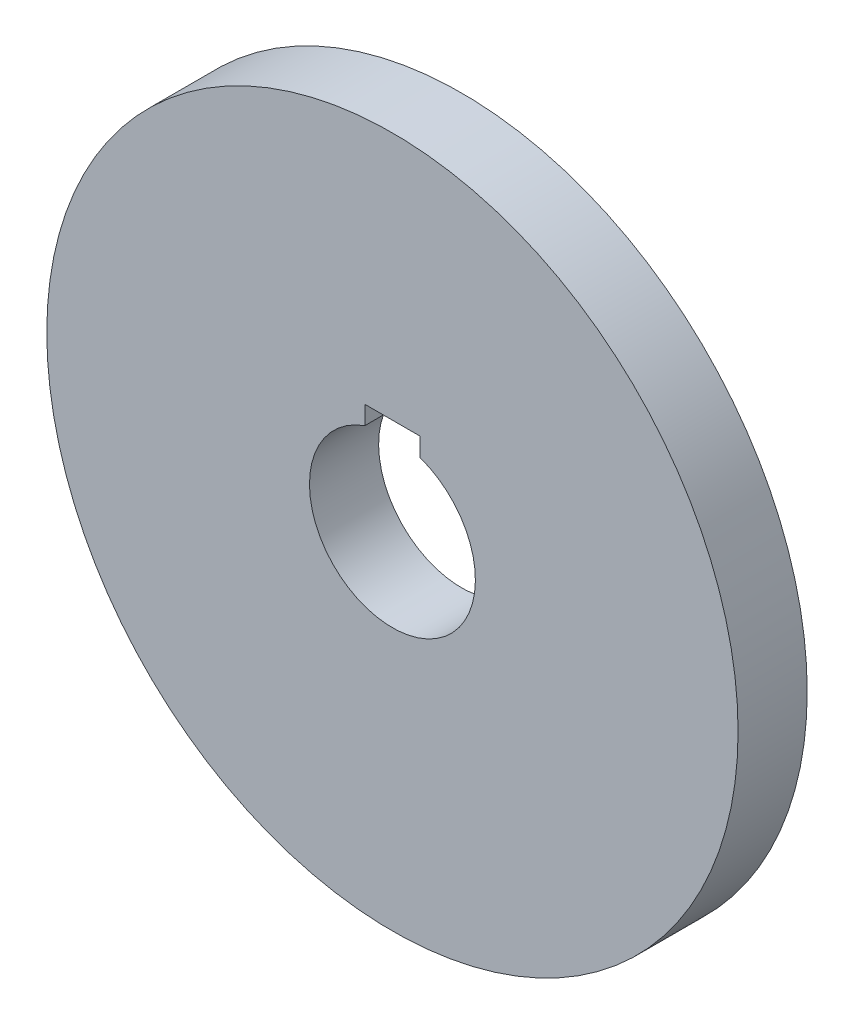
SolidWorks part; units mm, degrees
material "Acrylic (Medium-high impact)"
ref_plane "Front Plane" through (0, 0, 0) normal (0, 0, 1) x (1, 0, 0)
ref_plane "Top Plane" through (0, 0, 0) normal (0, 1, 0) x (1, 0, 0)
ref_plane "Right Plane" through (0, 0, 0) normal (1, 0, 0) x (0, 0, -1)
sketch "Sketch4" plane through (0, 0, 0) normal (0, 0, 1) x (1, 0, 0)
  circle A0 centre (0, 0) radius 25
  circle A1 centre (0, 0) radius 6
extrude "Boss-Extrude1" add sketch "Sketch4" along normal blind 5
sketch "Sketch5" plane through (0, 0, 5) normal (0, 0, 1) x (1, 0, 0)
  line L0 (0, 0) -> (0, 33.665) construction
  line L2 (-2, 7) -> (2, 7)
  line L3 (-2, 7) -> (-2, 5)
  line L4 (-2, 5) -> (2, 5)
  line L5 (2, 7) -> (2, 5)
  line L6 (-2, 7) -> (2, 5) construction
  line L7 (-2, 5) -> (2, 7) construction
  circle A0 centre (0, 0) radius 6 construction
  point P3 (0, 6)
  dimension "D1" = 4
  dimension "D2" = 7
extrude "Cut-Extrude1" cut sketch "Sketch5" against normal blind 5
